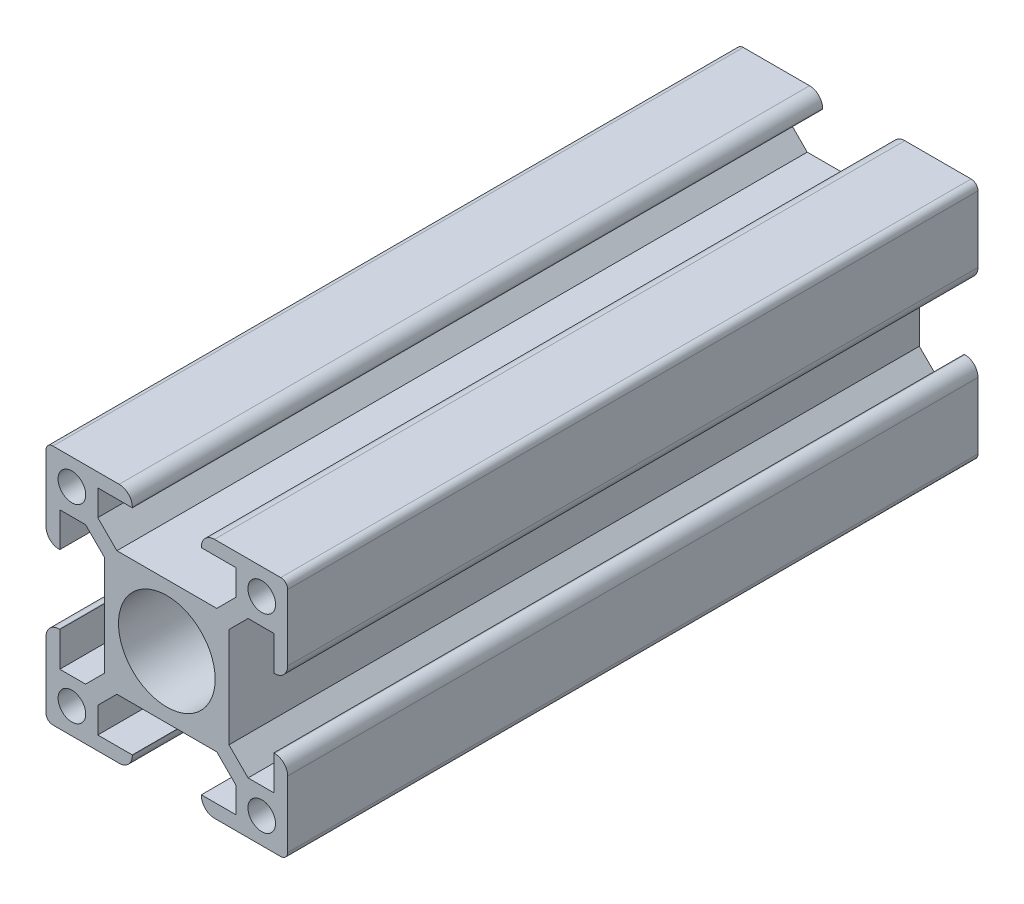
SolidWorks part; units mm, degrees
ref_plane "前视基准面" through (0, 0, 0) normal (0, 0, 1) x (1, 0, 0)
ref_plane "上视基准面" through (0, 0, 0) normal (0, 1, 0) x (1, 0, 0)
ref_plane "右视基准面" through (0, 0, 0) normal (1, 0, 0) x (0, 0, -1)
sketch "草图1" plane through (0, 0, 0) normal (0, 0, 1) x (1, 0, 0)
  line L0 (-16.0968, 15.9455) -> (-16.0968, 16.0455)
  line L1 (-17.9968, 17.9455) -> (-27.5968, 17.9455)
  line L2 (-28.5968, 16.9455) -> (-28.5968, 7.3455)
  line L3 (-26.6968, 5.4455) -> (-26.5968, 5.4455)
  line L4 (-16.0968, 15.9455) -> (-21.0968, 15.9455)
  line L5 (-26.5968, 10.4455) -> (-26.5968, 5.4455)
  line L6 (-20.0968, 7.6777) -> (-20.0968, -6.7868)
  line L7 (-18.329, -8.5545) -> (-3.8646, -8.5545)
  line L8 (-2.0968, -6.7868) -> (-2.0968, 7.6777)
  line L9 (-3.8646, 9.4455) -> (-18.329, 9.4455)
  line L10 (-26.5968, 10.4455) -> (-22.8646, 10.4455)
  line L11 (-21.0968, 12.2132) -> (-18.329, 9.4455)
  line L12 (-22.8646, 10.4455) -> (-20.0968, 7.6777)
  line L14 (-21.0968, 15.9455) -> (-21.0968, 12.2132)
  line L15 (-6.0968, 15.9455) -> (-6.0968, 16.0455)
  line L16 (-4.1968, 17.9455) -> (5.4032, 17.9455)
  line L17 (6.4032, 16.9455) -> (6.4032, 7.3455)
  line L18 (4.5032, 5.4455) -> (4.4032, 5.4455)
  line L19 (-6.0968, 15.9455) -> (-1.0968, 15.9455)
  line L20 (4.4032, 10.4455) -> (4.4032, 5.4455)
  line L21 (4.4032, 10.4455) -> (0.671, 10.4455)
  line L22 (-1.0968, 12.2132) -> (-3.8646, 9.4455)
  line L23 (0.671, 10.4455) -> (-2.0968, 7.6777)
  line L25 (-1.0968, 15.9455) -> (-1.0968, 12.2132)
  line L26 (-16.0968, -15.0545) -> (-16.0968, -15.1545)
  line L27 (-17.9968, -17.0545) -> (-27.5968, -17.0545)
  line L28 (-28.5968, -16.0545) -> (-28.5968, -6.4545)
  line L29 (-26.6968, -4.5545) -> (-26.5968, -4.5545)
  line L30 (-16.0968, -15.0545) -> (-21.0968, -15.0545)
  line L31 (-26.5968, -9.5545) -> (-26.5968, -4.5545)
  line L32 (-26.5968, -9.5545) -> (-22.8646, -9.5545)
  line L33 (-21.0968, -11.3223) -> (-18.329, -8.5545)
  line L34 (-22.8646, -9.5545) -> (-20.0968, -6.7868)
  line L36 (-21.0968, -15.0545) -> (-21.0968, -11.3223)
  line L37 (-6.0968, -15.0545) -> (-6.0968, -15.1545)
  line L38 (-4.1968, -17.0545) -> (5.4032, -17.0545)
  line L39 (6.4032, -16.0545) -> (6.4032, -6.4545)
  line L40 (4.5032, -4.5545) -> (4.4032, -4.5545)
  line L41 (-6.0968, -15.0545) -> (-1.0968, -15.0545)
  line L42 (4.4032, -9.5545) -> (4.4032, -4.5545)
  line L43 (4.4032, -9.5545) -> (0.671, -9.5545)
  line L44 (-1.0968, -11.3223) -> (-3.8646, -8.5545)
  line L45 (0.671, -9.5545) -> (-2.0968, -6.7868)
  line L47 (-1.0968, -15.0545) -> (-1.0968, -11.3223)
  arc A0 (-16.0968, 16.0455) -> (-17.9968, 17.9455) centre (-17.9968, 16.0455) ccw
  arc A1 (-27.5968, 17.9455) -> (-28.5968, 16.9455) centre (-27.5968, 16.9455) ccw
  arc A2 (-28.5968, 7.3455) -> (-26.6968, 5.4455) centre (-26.6968, 7.3455) ccw
  circle A3 centre (-11.0968, 0.4455) radius 7
  circle A4 centre (-24.8468, 14.1955) radius 2
  arc A5 (-4.1968, 17.9455) -> (-6.0968, 16.0455) centre (-4.1968, 16.0455) ccw
  arc A6 (6.4032, 16.9455) -> (5.4032, 17.9455) centre (5.4032, 16.9455) ccw
  arc A7 (4.5032, 5.4455) -> (6.4032, 7.3455) centre (4.5032, 7.3455) ccw
  circle A8 centre (2.6532, 14.1955) radius 2
  arc A9 (-17.9968, -17.0545) -> (-16.0968, -15.1545) centre (-17.9968, -15.1545) ccw
  arc A10 (-28.5968, -16.0545) -> (-27.5968, -17.0545) centre (-27.5968, -16.0545) ccw
  arc A11 (-26.6968, -4.5545) -> (-28.5968, -6.4545) centre (-26.6968, -6.4545) ccw
  circle A12 centre (-24.8468, -13.3045) radius 2
  arc A13 (-6.0968, -15.1545) -> (-4.1968, -17.0545) centre (-4.1968, -15.1545) ccw
  arc A14 (5.4032, -17.0545) -> (6.4032, -16.0545) centre (5.4032, -16.0545) ccw
  arc A15 (6.4032, -6.4545) -> (4.5032, -4.5545) centre (4.5032, -6.4545) ccw
  circle A16 centre (2.6532, -13.3045) radius 2
extrude "凸台-拉伸1" add sketch "草图1" along normal blind 100
